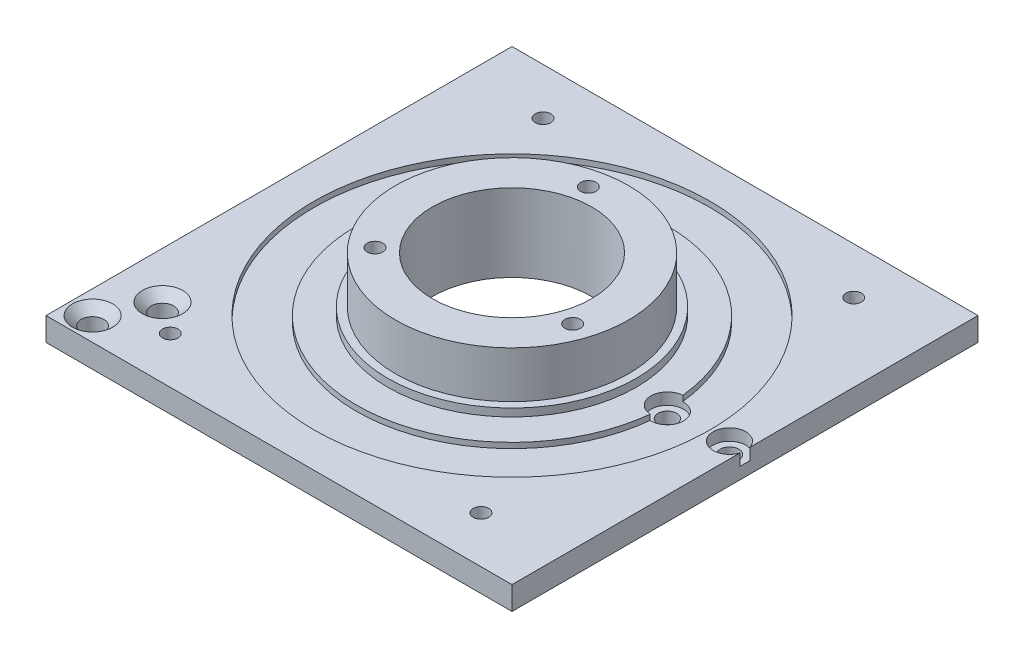
SolidWorks part; units mm, degrees
ref_plane "Front Plane" through (0, 0, 0) normal (0, 0, 1) x (1, 0, 0)
ref_plane "Top Plane" through (0, 0, 0) normal (0, 1, 0) x (1, 0, 0)
ref_plane "Right Plane" through (0, 0, 0) normal (1, 0, 0) x (0, 0, -1)
sketch "Sketch1" plane through (0, 0, 0) normal (0, 1, 0) x (1, 0, 0)
  line L1 (30, -30) -> (-30, -30)
  line L2 (30, -30) -> (30, 30)
  line L3 (30, 30) -> (-30, 30)
  line L4 (-30, -30) -> (-30, 30)
  line L5 (30, -30) -> (-30, 30) construction
  line L6 (30, 30) -> (-30, -30) construction
  point P0 (0, 0)
extrude "Boss-Extrude1" add sketch "Sketch1" along normal blind 3
sketch "Sketch2" plane through (0, 3, 0) normal (0, 1, 0) x (1, 0, 0)
  line L0 (-7, 0) -> (-6.6, 0) construction
  line L1 (-7, 4) -> (-5.2498, 4)
  line L2 (-7, -4) -> (-5.2498, -4)
  line L3 (0, -7) -> (0, -6.6) construction
  line L4 (-4, -7) -> (-4, -5.2498)
  line L5 (4, -7) -> (4, -5.2498)
  line L6 (5.2498, 4) -> (7, 4)
  line L7 (-4, 5.2498) -> (-4, 7)
  line L8 (6.6, 0) -> (7, 0) construction
  line L9 (0, 6.6) -> (0, 7) construction
  line L10 (5.2498, -4) -> (7, -4)
  line L11 (4, 5.2498) -> (4, 7)
  arc A0 (-4, 5.2498) -> (-5.2498, 4) centre (0, 0) ccw
  arc A2 (-7, 4) -> (-7, -4) centre (-7, 0) ccw
  arc A3 (7, -4) -> (7, 4) centre (7, 0) ccw
  arc A4 (-4, -7) -> (4, -7) centre (0, -7) ccw
  arc A5 (4, 7) -> (-4, 7) centre (0, 7) ccw
  arc A6 (5.2498, 4) -> (4, 5.2498) centre (0, 0) ccw
  arc A7 (4, -5.2498) -> (5.2498, -4) centre (0, 0) ccw
  arc A8 (-5.2498, -4) -> (-4, -5.2498) centre (0, 0) ccw
  point P5 (0, 0)
  point P11 (0, 0)
extrude "Cut-Extrude1" [suppressed] cut sketch "Sketch2" against normal through all
sketch "Sketch3" plane through (0, 3, 0) normal (0, 1, 0) x (1, 0, 0)
  circle A0 centre (-20, 24) radius 1
  circle A1 centre (20, 24) radius 1
  circle A2 centre (-20, -24) radius 1
  circle A3 centre (20, -24) radius 1
extrude "Cut-Extrude3" cut sketch "Sketch3" against normal through all
sketch "Sketch4" plane through (0, 0, 0) normal (0, -1, 0) x (1, 0, 0)
  line L0 (-20, 24) -> (20, -24) construction
  line L1 (-20, -24) -> (20, 24) construction
  point P11 (0, 0)
sketch "Sketch5" plane through (0, 0, 0) normal (0, -1, 0) x (1, 0, 0)
  circle A0 centre (0, 0) radius 10.25
extrude "Cut-Extrude4" cut sketch "Sketch5" against normal through all
sketch "Sketch6" plane through (0, 3, 0) normal (0, 1, 0) x (1, 0, 0)
  circle A0 centre (0, 0) radius 16
  circle A1 centre (0, 0) radius 10.25
extrude "Boss-Extrude2" add sketch "Sketch6" along normal blind 1
sketch "Sketch7" plane through (0, 3, 0) normal (0, 1, 0) x (1, 0, 0)
  line L0 (-20, 24) -> (20, -24) construction
  circle A0 centre (0, 0) radius 15
  circle A1 centre (0, 0) radius 10.25
extrude "Boss-Extrude3" add sketch "Sketch7" along normal blind 7
sketch "Sketch8" plane through (0, 3, 0) normal (0, 1, 0) x (1, 0, 0)
  circle A0 centre (-21, -21) radius 1.45
  circle A1 centre (-27, -27) radius 1.45
sketch "Sketch9" plane through (0, 3, 0) normal (0, 1, 0) x (1, 0, 0)
  circle A0 centre (-21, -21) radius 2.6
  circle A1 centre (-27, -27) radius 2.6
sketch "Sketch10" plane through (0, 3, 0) normal (0, 1, 0) x (1, 0, 0)
  circle A0 centre (-24, -21) radius 1.45
  circle A1 centre (-27, -27) radius 1.45
extrude "Stop_Mount_D2p9_Through" cut sketch "Sketch10" against normal blind 3.01
sketch "Sketch11" plane through (0, 3, 0) normal (0, 1, 0) x (1, 0, 0)
  circle A0 centre (-24, -21) radius 2.6
  circle A1 centre (-27, -27) radius 2.6
extrude "Stop_Mount_CSK_D5p2_90deg" cut sketch "Sketch11" against normal blind 1.15 draft 45
sketch "Sketch12" plane through (0, 0, 0) normal (0, -1, 0) x (1, 0, 0)
  circle A0 centre (20, -23) radius 1.45
  circle A1 centre (20, -17) radius 1.45
sketch "Sketch13" plane through (0, 0, 0) normal (0, -1, 0) x (1, 0, 0)
  circle A0 centre (27, -23) radius 1.45
  circle A1 centre (27, -17) radius 1.45
extrude "YTab_D2p9" cut sketch "Sketch13" against normal blind 3.01
sketch "Sketch14" plane through (0, 3, 0) normal (0, 1, 0) x (1, 0, 0)
  circle A0 centre (28, 0) radius 1.2
  circle A1 centre (20, 0) radius 1.2
extrude "GuideBlock1_D2p4" cut sketch "Sketch14" against normal blind 3.01
sketch "Sketch15" plane through (0, 3, 0) normal (0, 1, 0) x (1, 0, 0)
  circle A0 centre (28, 0) radius 2.1
  circle A1 centre (20, 0) radius 2.1
extrude "GuideBlock1_HeadCounterbore_D4p2" cut sketch "Sketch15" against normal blind 1.5
sketch "Sketch16" plane through (0, 3, 0) normal (0, 1, 0) x (1, 0, 0)
  circle A0 centre (0, 0) radius 25.5
  circle A1 centre (0, 0) radius 20
extrude "Rotating_Retainer_Head_Clearance_Annulus" cut sketch "Sketch16" against normal blind 0.7
sketch "Sketch17" plane through (0, 10, 0) normal (0, 1, 0) x (1, 0, 0)
  circle A0 centre (-9.3993, -8.2404) radius 1
  circle A1 centre (-2.4367, 12.2602) radius 1
  circle A2 centre (11.836, -4.0198) radius 1
extrude "Inner_Retainer_M2_Tapped_Envelope" cut sketch "Sketch17" against normal blind 4.3
sketch "Sketch18" plane through (0, 0, 0) normal (0, -1, 0) x (1, 0, 0)
  circle A0 centre (27, -23) radius 1.46
  circle A1 centre (27, -17) radius 1.46
extrude "YTab_Through_Hole_Backing_Restoration" add sketch "Sketch18" against normal blind 3
sketch "Sketch19" plane through (0, 0, 0) normal (0, -1, 0) x (1, 0, 0)
  circle A0 centre (27, -23) radius 1.25
  circle A1 centre (27, -17) radius 1.25
extrude "YTab_Blind_M2p5_Thread_Envelopes" cut sketch "Sketch19" against normal blind 2.6
